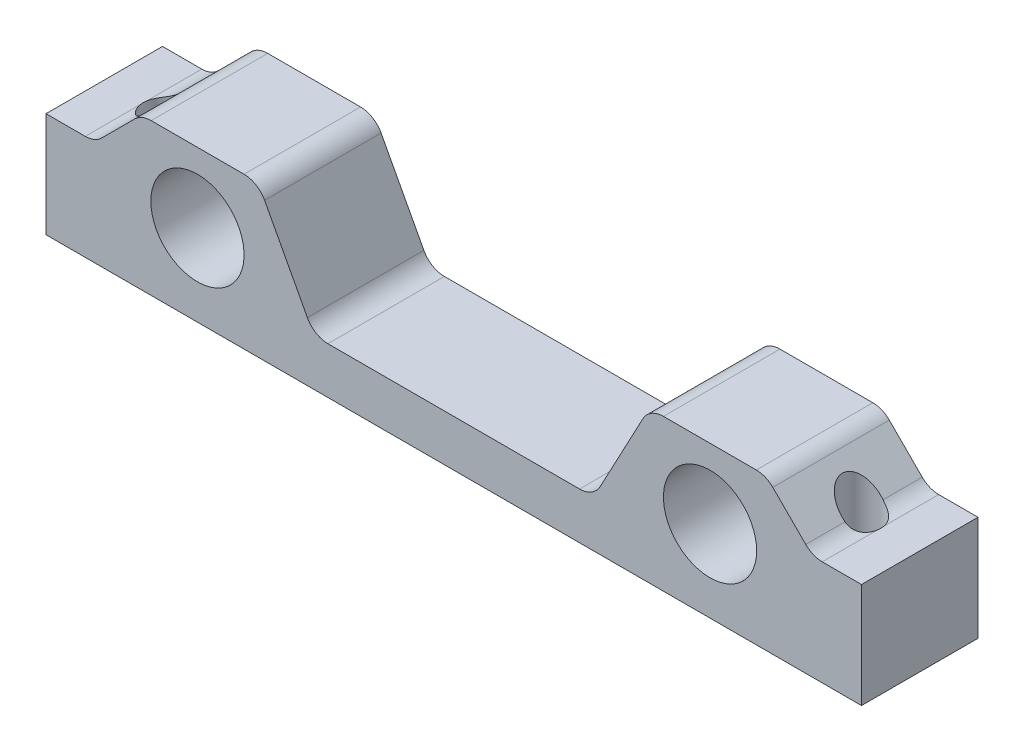
SolidWorks part; units mm, degrees
ref_plane "Front" through (0, 0, 0) normal (0, 0, 1) x (1, 0, 0)
ref_plane "Top" through (0, 0, 0) normal (0, 1, 0) x (1, 0, 0)
ref_plane "Right" through (0, 0, 0) normal (1, 0, 0) x (0, 0, -1)
other "Configuration Table"
sketch "Sketch1" plane through (0, 0, 0) normal (0, 0, 1) x (1, 0, 0)
  line L0 (-35, 0) -> (35, 0)
  line L1 (35, 0) -> (35, 9)
  line L2 (35, 9) -> (30.8, 9)
  line L3 (30.8, 9) -> (26.8, 13)
  line L4 (26.8, 13) -> (16.8, 13)
  line L5 (16.8, 13) -> (12, 4)
  line L6 (12, 4) -> (-12, 4)
  line L7 (0, 47.3629) -> (0, -33.0242) construction
  line L8 (-35, 0) -> (-35, 9)
  line L9 (-35, 9) -> (-30.8, 9)
  line L10 (-30.8, 9) -> (-26.8, 13)
  line L11 (-26.8, 13) -> (-16.8, 13)
  line L12 (-16.8, 13) -> (-12, 4)
  circle A0 centre (22, 7) radius 4
  circle A1 centre (-22, 7) radius 4
  dimension "D5" = 8
  dimension "D1" = 70
  dimension "D2" = 13
  dimension "D3" = 9
  dimension "D4" = 4
  dimension "D6" = 44
  dimension "D7" = 24
  dimension "D8" = 10
  dimension "D9" = 45
  dimension "D10" = 4.2
  dimension "D11" = 7
  dimension "D12" = 3
  dimension "D13" = 2
extrude "Boss-Extrude1" add sketch "Sketch1" along normal mid plane 10
fillet "Fillet1" radius 2 8 edges at (-30.8, 9, 0) (-26.8, 13, 0) (-16.8, 13, 0) (-12, 4, 0) (12, 4, 0) (16.8, 13, 0) (26.8, 13, 0) (30.8, 9, 0)
hole_wizard "M4 Tapped Hole1" positions "Sketch5" profile "Sketch4" tap size "M4" standard "ISO" end condition through all
sketch "Sketch5" plane through (0, 0, 0) normal (0, -1, 0) x (-1, 0, 0)
  line L0 (0, 16.5485) -> (0, -16.3803) construction
  point P0 (-30, 0)
  point P2 (30, 0)
  dimension "D1" = 60
sketch "Sketch4" plane through (30, 0, 0) normal (1, 0, 0) x (0, 0, -1)
  line L0 (0, 0) -> (0, 13)
  line L1 (0, 13) -> (1.65, 13)
  line L2 (1.65, 13) -> (1.65, 0.375)
  line L3 (1.65, 0.375) -> (2.025, 0)
  line L5 (2.025, 0) -> (0, 0)
  line L6 (-1.65, 0.375) -> (-2.025, 0) construction
  line L11 (0, -6.35) -> (0, 107.95) construction
  dimension "Thru Tap Drill Dia." = 3.3
  dimension "Thru Tap Drill Depth" = 13
  dimension "Near C'Sink Dia." = 4.05
  dimension "Near C'Sink Angle" = 90
cosmetic thread "Hole Thread1"
cosmetic thread "Hole Thread2"
